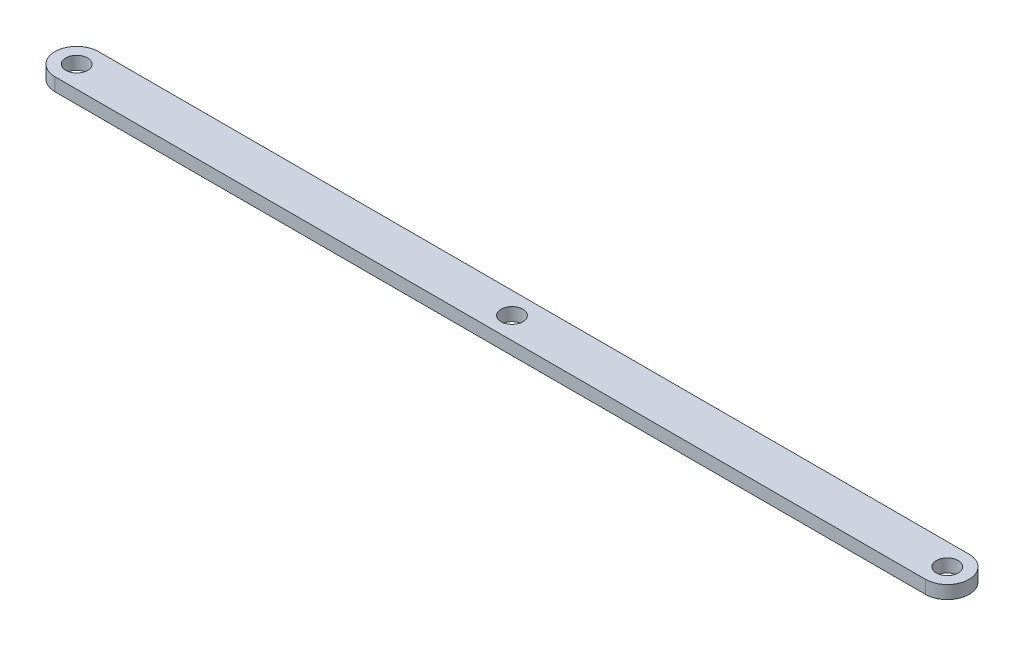
SolidWorks part; units mm, degrees
ref_plane "Front Plane" through (0, 0, 0) normal (0, 0, 1) x (1, 0, 0)
ref_plane "Top Plane" through (0, 0, 0) normal (0, 1, 0) x (1, 0, 0)
ref_plane "Right Plane" through (0, 0, 0) normal (1, 0, 0) x (0, 0, -1)
sketch "Sketch2" plane through (0, 0, 0) normal (0, 1, 0) x (1, 0, 0)
  line L0 (-100, 0) -> (100, 0) construction
  line L1 (-100, 5) -> (100, 5)
  line L2 (-100, -5) -> (100, -5)
  arc A0 (-100, 5) -> (-100, -5) centre (-100, 0) ccw
  arc A1 (100, -5) -> (100, 5) centre (100, 0) ccw
  point P2 (0, 0)
  dimension "D1" = 10
  dimension "D2" = 200
extrude "Boss-Extrude1" add sketch "Sketch2" along normal blind 3
sketch "Sketch3" plane through (0, 3, 0) normal (0, 1, 0) x (1, 0, 0)
  circle A0 centre (100, 0) radius 2.5
  dimension "D1" = 5
extrude "Cut-Extrude1" cut sketch "Sketch3" against normal up to next
mirror "Mirror1" about plane through (0, 0, 0) normal (1, 0, 0) of "Cut-Extrude1"
sketch "Sketch4" plane through (0, 0, 0) normal (0, -1, 0) x (-1, 0, 0)
  circle A0 centre (0, 0) radius 2.5
  dimension "D1" = 5
extrude "Boss-Extrude2" [suppressed] add sketch "Sketch4" along normal blind 15
sketch "Sketch5" plane through (0, 0, 0) normal (0, -1, 0) x (1, 0, 0)
  circle A0 centre (0, 0) radius 2.5
  dimension "D1" = 5
extrude "Cut-Extrude2" cut sketch "Sketch5" against normal up to next
sketch "Sketch6" [suppressed] plane through (0, 0, 0) normal (0, -1, 0) x (1, 0, 0)
  line L0 (100, -5) -> (-100, -5) construction
  line L1 (-100, 5) -> (100, 5) construction
  circle A0 centre (21, 0) radius 2.5
  circle A1 centre (31, 0) radius 2.5
  circle A2 centre (-32, 0) radius 2.5
  circle A3 centre (-42, 0) radius 2.5
  dimension "D1" = 5
  dimension "D4" = 5
  dimension "D8" = 5
  dimension "D10" = 5
  dimension "D2" = 21
  dimension "D3" = 5
  dimension "D5" = 31
  dimension "D6" = 5
  dimension "D7" = 32
  dimension "D9" = 5
  dimension "D11" = 42
  dimension "D12" = 5
extrude "Cut-Extrude3" [suppressed] cut sketch "Sketch6" against normal up to next
